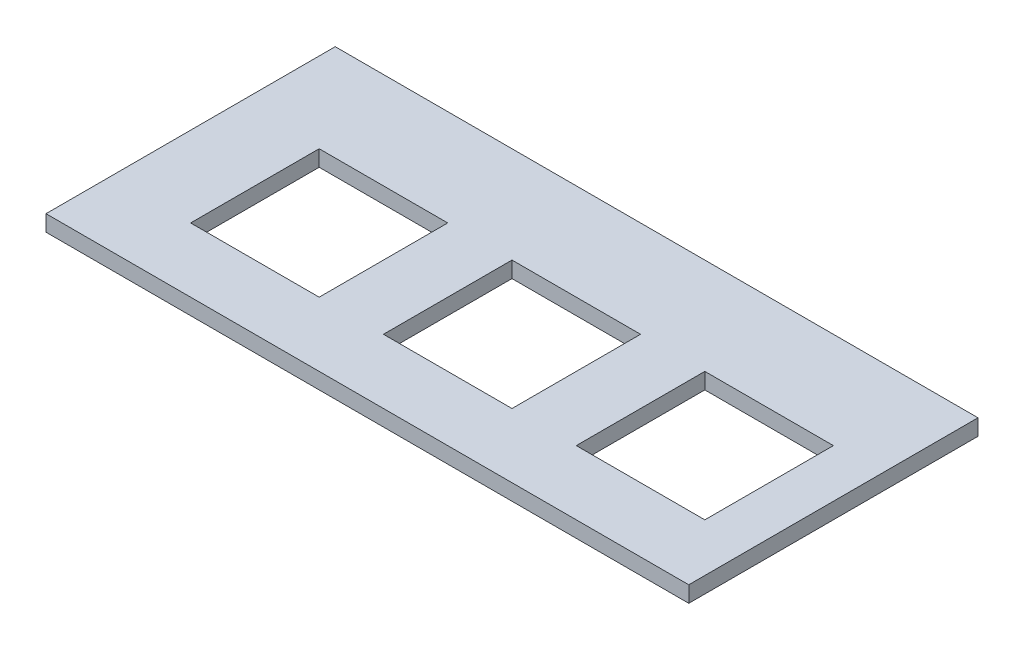
SolidWorks part; units mm, degrees
material "Balsa"
ref_plane "Plan de face" through (0, 0, 0) normal (0, 0, 1) x (1, 0, 0)
ref_plane "Plan de dessus" through (0, 0, 0) normal (0, 1, 0) x (1, 0, 0)
ref_plane "Plan de droite" through (0, 0, 0) normal (1, 0, 0) x (0, 0, -1)
sketch "Esquisse1" plane through (0, 0, 0) normal (0, 1, 0) x (1, 0, 0)
  line L5 (0, 0) -> (-400, 0)
  line L6 (0, 0) -> (0, 180)
  line L7 (0, 180) -> (-400, 180)
  line L8 (-400, 0) -> (-400, 180)
  dimension "D1" = 400
  dimension "D2" = 180
extrude "Boss.-Extru.1" add sketch "Esquisse1" along normal blind 10
sketch "Esquisse2" plane through (0, 10, 0) normal (0, 1, 0) x (1, 0, 0)
  line L0 (0, 180) -> (-400, 180) construction
  line L1 (-350, 120) -> (-270, 120)
  line L2 (-350, 120) -> (-350, 40)
  line L3 (-350, 40) -> (-270, 40)
  line L4 (-270, 120) -> (-270, 40)
  line L5 (-230, 120) -> (-150, 120)
  line L6 (-230, 120) -> (-230, 40)
  line L7 (-230, 40) -> (-150, 40)
  line L8 (-150, 120) -> (-150, 40)
  line L9 (-110, 120) -> (-30, 120)
  line L10 (-110, 120) -> (-110, 40)
  line L11 (-110, 40) -> (-30, 40)
  line L12 (-30, 120) -> (-30, 40)
  line L13 (-400, 180) -> (-400, 0) construction
  dimension "D1" = 80
  dimension "D2" = 80
  dimension "D3" = 60
  dimension "D4" = 40
  dimension "D5" = 80
  dimension "D6" = 80
  dimension "D7" = 60
  dimension "D8" = 80
  dimension "D9" = 80
  dimension "D10" = 40
  dimension "D11" = 60
  dimension "D12" = 50
extrude "Enlèv. mat.-Extru.1" cut sketch "Esquisse2" against normal blind 10
